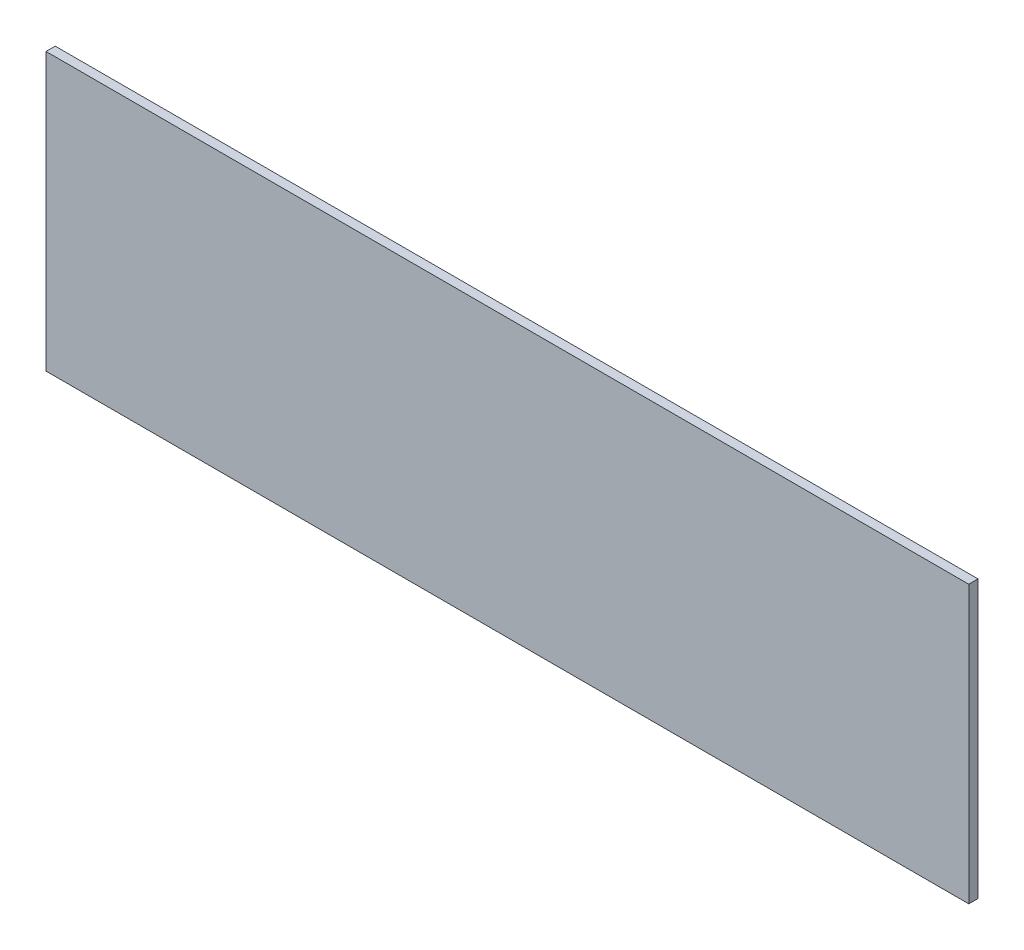
SolidWorks part; units mm, degrees
ref_plane "Front Plane" through (0, 0, 0) normal (0, 0, 1) x (1, 0, 0)
ref_plane "Top Plane" through (0, 0, 0) normal (0, 1, 0) x (1, 0, 0)
ref_plane "Right Plane" through (0, 0, 0) normal (1, 0, 0) x (0, 0, -1)
sketch "Sketch1" plane through (0, 0, 0) normal (0, 0, 1) x (1, 0, 0)
  line L1 (0, 0) -> (500, 0)
  line L2 (0, 0) -> (0, -150)
  line L3 (0, -150) -> (500, -150)
  line L4 (500, 0) -> (500, -150)
  dimension "D1" = 500
  dimension "D2" = 150
extrude "Boss-Extrude1" add sketch "Sketch1" along normal blind 5
